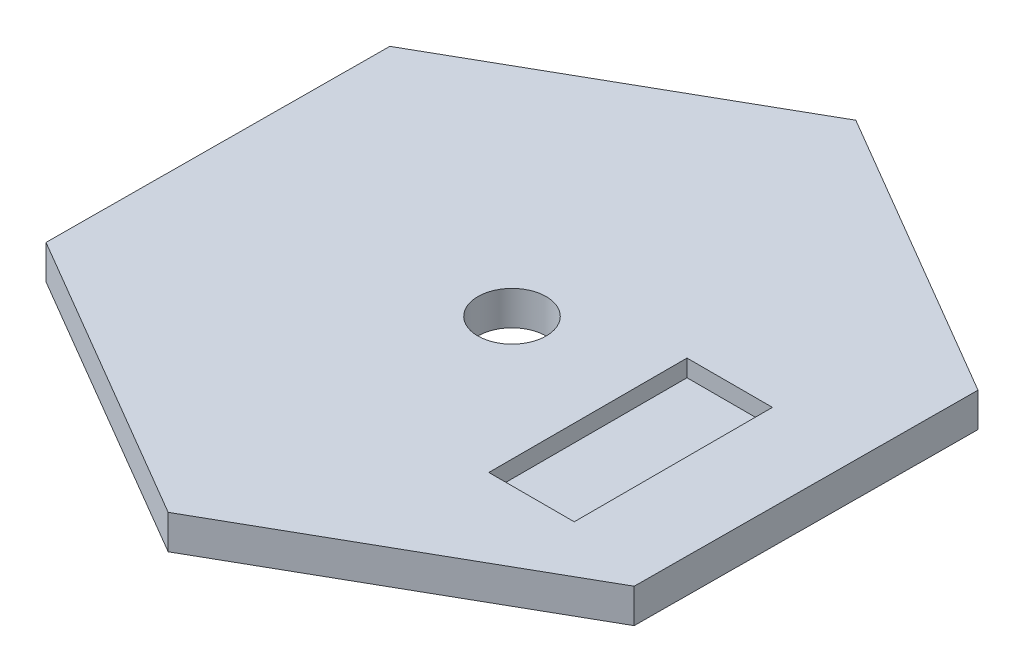
SolidWorks part; units mm, degrees
ref_plane "Alzado" through (0, 0, 0) normal (0, 0, 1) x (1, 0, 0)
ref_plane "Planta" through (0, 0, 0) normal (0, 1, 0) x (1, 0, 0)
ref_plane "Vista lateral" through (0, 0, 0) normal (1, 0, 0) x (0, 0, -1)
sketch "Croquis1" plane through (0, 0, 0) normal (0, 1, 0) x (1, 0, 0)
  line L1 (-86.2913, 50.5352) -> (-86.9105, -49.4628)
  line L2 (-86.9105, -49.4628) -> (-0.6191, -99.9981)
  line L3 (-0.6191, -99.9981) -> (86.2913, -50.5352)
  line L4 (86.2913, -50.5352) -> (86.9105, 49.4628)
  line L5 (86.9105, 49.4628) -> (0.6191, 99.9981)
  line L6 (0.6191, 99.9981) -> (-86.2913, 50.5352)
  circle A0 centre (0, 0) radius 86.6025 construction
extrude "Saliente-Extruir1" add sketch "Croquis1" along normal blind 10
sketch "Croquis2" plane through (0, 10, 0) normal (0, 1, 0) x (1, 0, 0)
  circle A0 centre (0, 0) radius 10
  dimension "D1" = 20
extrude "Cortar-Extruir1" cut sketch "Croquis2" against normal blind 10
sketch "Croquis3" plane through (0, 10, 0) normal (0, 1, 0) x (1, 0, 0)
  line L1 (36.1933, 15.0209) -> (61.1933, 15.0209)
  line L2 (36.1933, 15.0209) -> (36.1933, -42.9791)
  line L3 (36.1933, -42.9791) -> (61.1933, -42.9791)
  line L4 (61.1933, 15.0209) -> (61.1933, -42.9791)
  dimension "D1" = 58
  dimension "D2" = 25
extrude "Cortar-Extruir2" cut sketch "Croquis3" against normal blind 5
